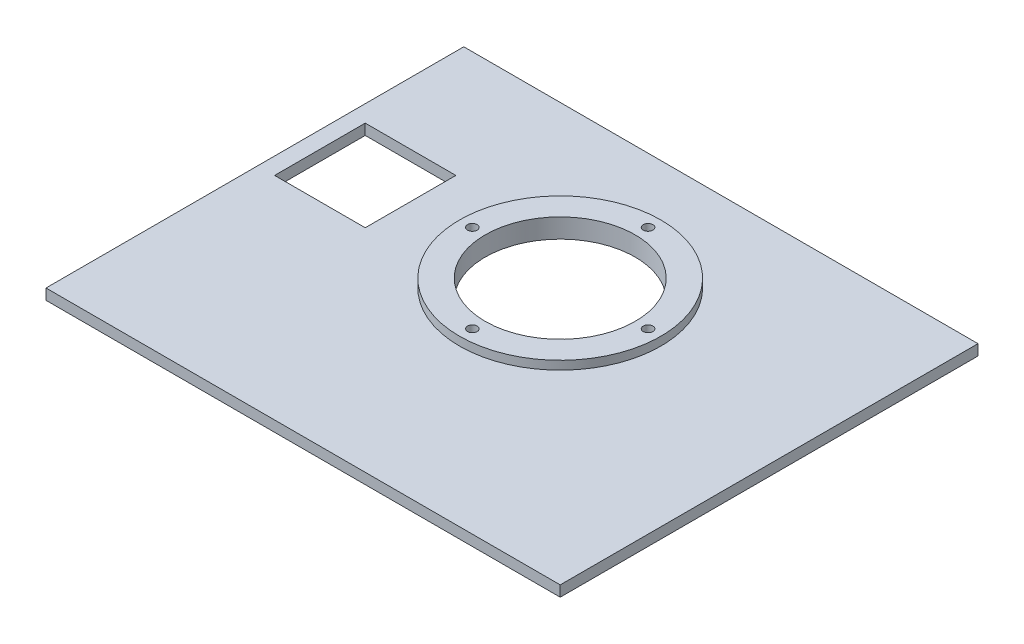
SolidWorks part; units mm, degrees
material "ABS generico"
ref_plane "Piano frontale" through (0, 0, 0) normal (0, 0, 1) x (1, 0, 0)
ref_plane "Piano superiore" through (0, 0, 0) normal (0, 1, 0) x (1, 0, 0)
ref_plane "Piano destro" through (0, 0, 0) normal (1, 0, 0) x (0, 0, -1)
sketch "Schizzo1" plane through (0, 0, 0) normal (0, 1, 0) x (1, 0, 0)
  line L0 (-120, 75) -> (120, 75)
  line L1 (-120, 75) -> (-120, -120)
  line L2 (-120, -120) -> (120, -120)
  line L3 (120, -120) -> (120, 75)
  line L4 (0, -120) -> (0, 75) construction
  circle A1 centre (0, 0) radius 35
  dimension "D1" = 120
  dimension "D2" = 70
  dimension "D3" = 75
  dimension "D4" = 240
extrude "Estrusione-Estrusione1" add sketch "Schizzo1" along normal blind 5
sketch "Schizzo3" plane through (0, 5, 0) normal (0, 1, 0) x (1, 0, 0)
  circle A0 centre (0, 0) radius 47
  circle A1 centre (0, 0) radius 35
  dimension "D1" = 94
extrude "Estrusione-Estrusione2" add sketch "Schizzo3" along normal blind 4
sketch "Schizzo5" plane through (0, 0, 0) normal (0, -1, 0) x (-1, 0, 0)
  line L0 (0, 0) -> (0, 41) construction
  circle A0 centre (0, 0) radius 41 construction
  point P4 (0, 41)
  point P6 (41, 0)
  point P8 (0, -41)
  point P10 (-41, 0)
  dimension "D1" = 82
hole_wizard "Foro per Vite M3-1" positions "Schizzo5" profile "Schizzo6" hole size "M3" standard "ISO"
sketch "Schizzo6" plane through (41, 0, 0) normal (1, 0, 0) x (0, 0, -1)
  line L0 (0, 0) -> (0, 19.4519)
  line L1 (0, 19.4519) -> (2.25, 18.1)
  line L2 (2.25, 18.1) -> (2.25, 0)
  line L5 (2.25, 0) -> (0, 0)
  line L10 (0, 19.4519) -> (-2.25, 18.1) construction
  line L11 (0, -6.35) -> (0, 107.95) construction
  dimension "Hole Dia." = 4.5
  dimension "Hole Depth" = 18.1
  dimension "Drill Angle" = 118
sketch "Schizzo7" plane through (0, 5, 0) normal (0, 1, 0) x (1, 0, 0)
  line L0 (-112.15, 21.15) -> (-69.85, -21.15) construction
  line L1 (-69.85, -21.15) -> (-112.15, -21.15)
  line L2 (-69.85, -21.15) -> (-69.85, 21.15)
  line L3 (-69.85, 21.15) -> (-112.15, 21.15)
  line L4 (-112.15, -21.15) -> (-112.15, 21.15)
  line L5 (-112.15, -21.15) -> (-69.85, 21.15) construction
  line L6 (-91, 0) -> (0, 0) construction
  point P4 (-91, 0)
  dimension "D1" = 91
  dimension "D2" = 42.3
extrude "Taglio-Estrusione1" cut sketch "Schizzo7" against normal blind 14
sketch "Schizzo8" plane through (0, 5, 0) normal (0, 1, 0) x (1, 0, 0)
  line L0 (0, -86) -> (0, -50)
  line L1 (0, 0) -> (-42.3513, 26.5776) construction
  line L2 (0, 0) -> (0, -50) construction
  line L3 (33.9037, -36.7496) -> (78.9041, -58.5434)
  line L4 (42.3513, 26.5776) -> (105.3517, -3.9337)
  line L5 (78.9041, -58.5434) -> (105.3517, -3.9337)
  line L6 (-107.116, -47.6911) -> (107.116, 47.6911) construction
  line L8 (120, 75) -> (253.8965, 75) construction
  line L9 (135.0175, 70) -> (267.7358, 70) construction
  circle A0 centre (0, 0) radius 50 construction
  arc A1 (-42.3513, 26.5776) -> (0, -50) centre (0, 0) ccw
  arc A2 (98.8175, -17.4256) -> (-42.3513, 26.5776) centre (0, -86) ccw construction
  arc A3 (-38.2314, 23.9922) -> (0, -45.1361) centre (0, 0) ccw
  arc A4 (33.9037, -36.7496) -> (-33.9037, -36.7496) centre (0, -86) ccw construction
  circle A5 centre (0, 0) radius 50
  circle A6 centre (195, -55) radius 117.5 construction
  circle A7 centre (195, -55) radius 41.5 construction
  circle A8 centre (195, -55) radius 97.5 construction
  circle A9 centre (195, -55) radius 125 construction
  point P17 (0, 0)
  point P24 (0, 0)
  point P28 (0, -77.4269)
  point P29 (0, -77.4269)
  point P30 (-107.116, -47.6911)
  point P31 (0, 0)
  point P32 (0, 0)
  point P36 (0, -85.786)
  point P37 (0, 0)
  dimension "D1" = 100
  dimension "D4" = 20
  dimension "D5" = 76
  dimension "D6" = 195
  dimension "D8" = 5
  dimension "D7" = 250
  dimension "D2" = 70
  dimension "D3" = 50
  dimension "D9" = 195
  dimension "D10" = 66
  dimension "D11" = 36
